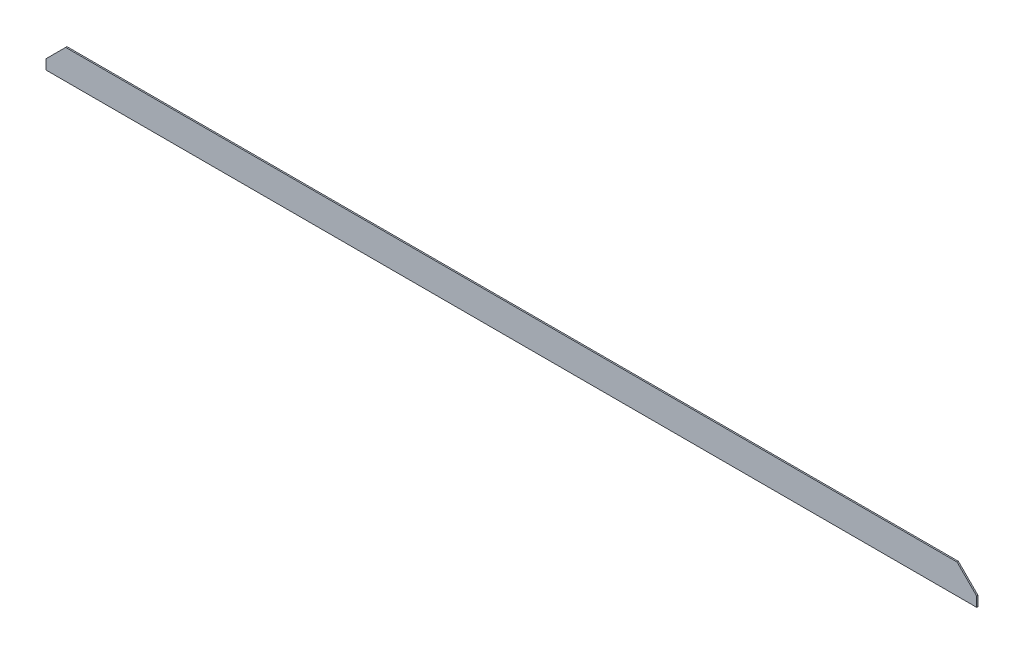
SolidWorks part; units mm, degrees
ref_plane "Front Plane" through (0, 0, 0) normal (0, 0, 1) x (1, 0, 0)
ref_plane "Top Plane" through (0, 0, 0) normal (0, 1, 0) x (1, 0, 0)
ref_plane "Right Plane" through (0, 0, 0) normal (1, 0, 0) x (0, 0, -1)
sketch "Sketch1" plane through (0, 0, 0) normal (0, 0, 1) x (1, 0, 0)
  line L1 (-710.5, -22.5) -> (710.5, -22.5)
  line L2 (-710.5, -22.5) -> (-710.5, 22.5)
  line L3 (-710.5, 22.5) -> (710.5, 22.5)
  line L4 (710.5, -22.5) -> (710.5, 22.5)
  line L5 (-710.5, -22.5) -> (710.5, 22.5) construction
  line L6 (-710.5, 22.5) -> (710.5, -22.5) construction
  point P0 (0, 0)
  dimension "D1" = 1421
  dimension "D2" = 45
extrude "Boss-Extrude1" add sketch "Sketch1" along normal blind 2
chamfer "Chamfer1" distance 30 angle 45 2 edges at (710.5, 22.5, 1) (-710.5, 22.5, 1)
